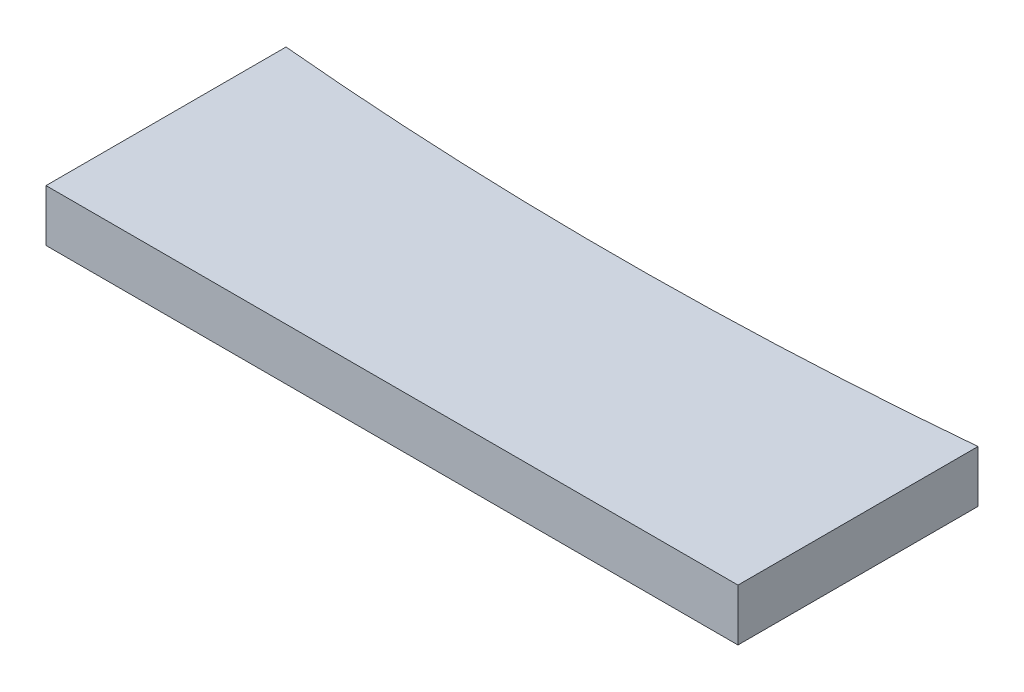
SolidWorks part; units mm, degrees
material "PTFE (general)"
ref_plane "Front Plane" through (0, 0, 0) normal (0, 0, 1) x (1, 0, 0)
ref_plane "Top Plane" through (0, 0, 0) normal (0, 1, 0) x (1, 0, 0)
ref_plane "Right Plane" through (0, 0, 0) normal (1, 0, 0) x (0, 0, -1)
sketch "Sketch1" plane through (0, 0, 0) normal (0, 1, 0) x (1, 0, 0)
  line L0 (-5.08, -55.3298) -> (-5.08, -58.5174)
  line L1 (5.08, -55.3298) -> (5.08, -58.5174)
  line L2 (-5.08, -58.8541) -> (5.08, -58.8541)
  line L3 (-5.08, -58.5174) -> (-5.08, -58.8541)
  line L4 (5.08, -58.5174) -> (5.08, -58.8541)
  line L5 (12.7, -54.0916) -> (12.7, -58.8541) construction
  line L6 (12.7, -58.8541) -> (5.08, -58.8541) construction
  line L7 (0, -55.5625) -> (0, -60.0923) construction
  circle A0 centre (0, 0) radius 55.5625
  circle A1 centre (0, 0) radius 58.7375
  dimension "D1" = 111.125
  dimension "D3" = 5.08
  dimension "D4" = 5.08
  dimension "D5" = 12.7
  dimension "D6" = 4.7625
  dimension "D2" = 3.175
extrude "Boss-Extrude1" add sketch "Sketch1" along normal blind 0.762 contours L0 A1 L1 A0 | A1 L3 L2 | A1 L2 L4
equation "\"Middle Coupler Inner Daimeter\"= 3.875in"
equation "\"Middle Coupler  Wall Thickness\" = 0.25in"
equation "\"Middle Coupler Bottom Thickness\"= 0.2in"
equation "\"Bearing Rail Offset\"= 0.45in"
equation "\"3-56 UNF Tap\"= 0.089in"
equation "\"3-56 UNF Clearance\"= 0.104in"
equation "\"Ball Bearing Distance\"= 0.03in"
equation "\"TCA Outer Diameter\" = 6in"
equation "\"D1@Sketch1\"=\"Middle Coupler Inner Daimeter\"+0.5"
equation "\"D2@Sketch1\"=1/8"
equation "\"Interstage Aeroframe Wall Thickness\" = 0.072in"
equation "\"Compression Spring OD\"= 0.42in"
equation "\"10-24 Tap\"= 0.157in"
equation "\"10-24 Clearance\"= 0.196in"
equation "\"Lower Stage Fuselage Wall Thickness\" = 0.25in"
equation "\"6-32 Tap\" = 0.107in"
equation "\"1/4-20 Tap\" = 0.201in"
equation "\"3-48 Tap\"= 0.079in"
equation "\"3-48 Clearance\" = 0.104in"
equation "\"6-32 Clearance\" = 0.144"
equation "\"12-24 Tap\" = 0.177in"
equation "\"D6@Sketch1\"=3/16"
